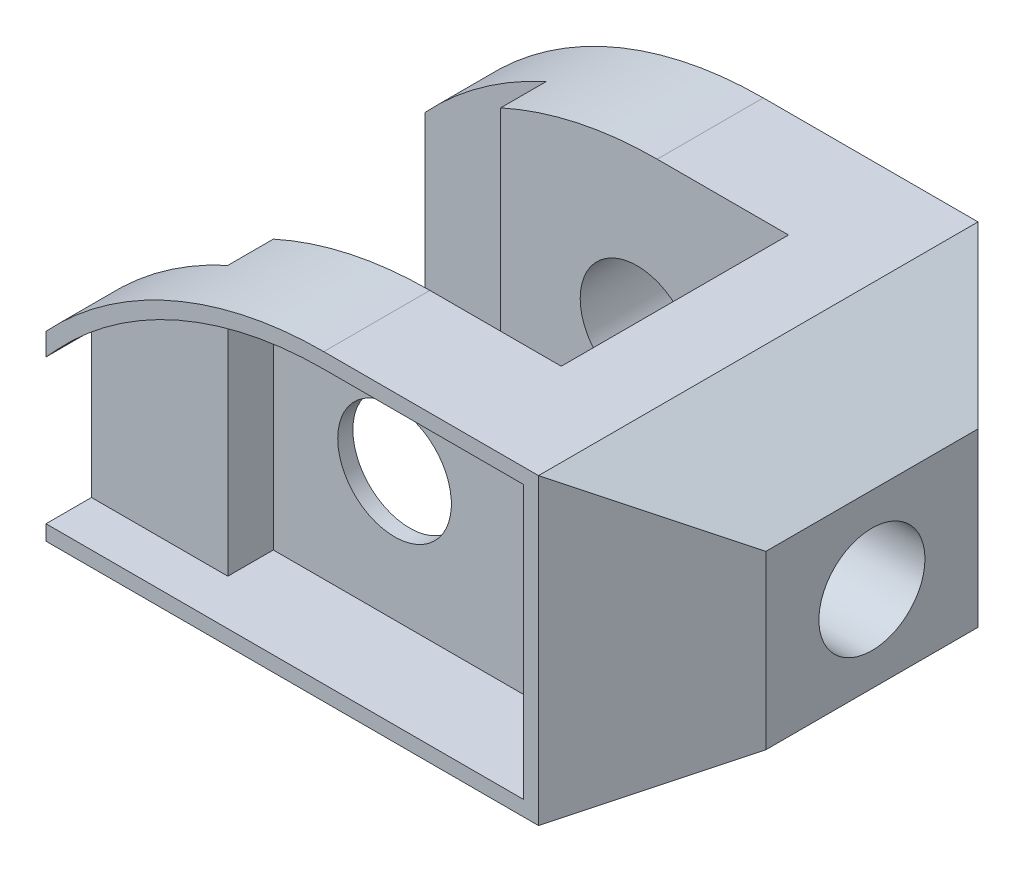
SolidWorks part; units mm, degrees
material "1060 Alloy"
ref_plane "Front Plane" through (0, 0, 0) normal (0, 0, 1) x (1, 0, 0)
ref_plane "Top Plane" through (0, 0, 0) normal (0, 1, 0) x (1, 0, 0)
ref_plane "Right Plane" through (0, 0, 0) normal (1, 0, 0) x (0, 0, -1)
sketch "Sketch1" plane through (0, 0, 0) normal (0, 0, 1) x (1, 0, 0)
  line L0 (0, 0) -> (65, 0)
  line L1 (65, 0) -> (80, 8.6603)
  line L2 (80, 8.6603) -> (80, 31.3397)
  line L3 (80, 31.3397) -> (65, 40)
  line L4 (65, 40) -> (36.6606, 40)
  line L5 (0, 0) -> (0, 24)
  arc A0 (36.6606, 40) -> (0, 24) centre (36.6606, -10) ccw
  circle A1 centre (34, 19) radius 7.5
  dimension "D8" = 50
  dimension "D9" = 15
  dimension "D10" = 19
  dimension "D1" = 65
  dimension "D2" = 40
  dimension "D3" = 15
  dimension "D4" = 15
  dimension "D5" = 30
  dimension "D6" = 30
  dimension "D7" = 24
  dimension "D11" = 31
extrude "Boss-Extrude1" add sketch "Sketch1" along normal mid plane 58
sketch "Sketch2" plane through (0, 0, 0) normal (0, 1, 0) x (1, 0, 0)
  line L0 (0, -29) -> (0, 29) construction
  line L1 (0, 21) -> (16, 21)
  line L2 (0, 21) -> (0, -21)
  line L3 (0, -21) -> (16, -21)
  line L4 (16, 21) -> (16, 15)
  line L5 (36.6606, -29) -> (36.6606, 29) construction
  line L6 (16, 15) -> (54, 15)
  line L8 (16, -15) -> (54, -15)
  line L9 (54, 15) -> (54, -15)
  line L10 (16, -15) -> (16, -21)
  line L12 (36.6606, 29) -> (0, 29) construction
  line L13 (0, -29) -> (36.6606, -29) construction
  line L14 (65, -29) -> (65, 29) construction
  point P6 (36.6606, 0)
  dimension "D1" = 8
  dimension "D2" = 8
  dimension "D3" = 11
  dimension "D4" = 30
  dimension "D5" = 6
  dimension "D6" = 16
extrude "Cut-Extrude1" cut sketch "Sketch2" along normal blind 58
sketch "Sketch3" plane through (0, 0, 0) normal (0, 1, 0) x (1, 0, 0)
  line L0 (80, 29) -> (65, 29)
  line L1 (65, 29) -> (80, 14)
  line L2 (80, -29) -> (80, 29) construction
  line L3 (80, -29) -> (65, -29)
  line L4 (65, -29) -> (80, -14)
  line L5 (65, 29) -> (36.6606, 29) construction
  line L7 (65, -29) -> (36.6606, -29) construction
  line L8 (80, -29) -> (80, -14)
  line L9 (80, 14) -> (80, 29)
  dimension "D1" = 45
  dimension "D2" = 45
extrude "Cut-Extrude2" cut sketch "Sketch3" along normal blind 58
sketch "Sketch7" plane through (80, 0, 0) normal (1, 0, 0) x (0, 0, -1)
  line L1 (-29, 40) -> (-29, 0) construction
  line L2 (-29, 0) -> (29, 0) construction
  circle A0 centre (0, 20) radius 7
  dimension "D1" = 14
  dimension "D2" = 29
  dimension "D3" = 20
extrude "Cut-Extrude3" cut sketch "Sketch7" against normal blind 58
sketch "Sketch8" plane through (0, 0, 29) normal (0, 0, 1) x (1, 0, 0)
  line L0 (0, 2) -> (63, 2)
  line L1 (63, 2) -> (63, 38)
  line L2 (63, 38) -> (36.6606, 38)
  line L3 (1.4664, 22.64) -> (0, 21.0588)
  line L4 (0, 0) -> (65, 0)
  line L5 (65, 0) -> (65, 40)
  line L6 (65, 40) -> (36.6606, 40)
  line L7 (0, 24) -> (0, 0)
  line L8 (0, 0) -> (65, 0)
  line L9 (65, 0) -> (65, 40)
  line L10 (65, 40) -> (36.6606, 40)
  line L11 (0, 21.0588) -> (0, 2)
  line L12 (16, 35.5317) -> (16, 0) construction
  line L13 (16, 33.326) -> (16, 2) construction
  line L14 (18, 34.2242) -> (18, 2)
  arc A0 (36.6606, 38) -> (1.4664, 22.64) centre (36.6606, -10) ccw
  arc A1 (36.6606, 40) -> (0, 24) centre (36.6606, -10) ccw
  arc A2 (36.6606, 40) -> (0, 24) centre (36.6606, -10) ccw
  dimension "D2" = 2
  dimension "D3" = 2
  dimension "D1" = 0
extrude "Cut-Extrude4" cut sketch "Sketch8" against normal blind 6 contours L2 A0 L3 L11 L0 L1
sketch "Sketch9" plane through (0, 0, 23) normal (0, 0, 1) x (1, 0, 0)
  line L0 (16, 35.5317) -> (16, 0) construction
  line L1 (16, 33.326) -> (16, 2) construction
  line L2 (18, 34.2242) -> (18, 2)
  line L5 (63, 2) -> (63, 38)
  line L6 (63, 38) -> (36.6606, 38)
  line L7 (1.4664, 22.64) -> (0, 21.0588)
  line L8 (0, 21.0588) -> (0, 2)
  line L9 (0, 2) -> (63, 2)
  line L10 (63, 2) -> (63, 38)
  line L11 (63, 38) -> (36.6606, 38)
  line L12 (1.4664, 22.64) -> (0, 21.0588)
  line L13 (0, 21.0588) -> (0, 2)
  line L14 (18, 2) -> (63, 2)
  arc A1 (36.6606, 38) -> (1.4664, 22.64) centre (36.6606, -10) ccw
  arc A2 (36.6606, 38) -> (18, 34.2242) centre (36.6606, -10) ccw
  dimension "D2" = 2
  dimension "D1" = 0
extrude "Cut-Extrude5" cut sketch "Sketch9" against normal blind 6 contours L11 A2 L2 L14 L10
equation "\"A\"= 58mm"
equation "\"B\"= 40mm"
equation "\"C\"= 65mm"
